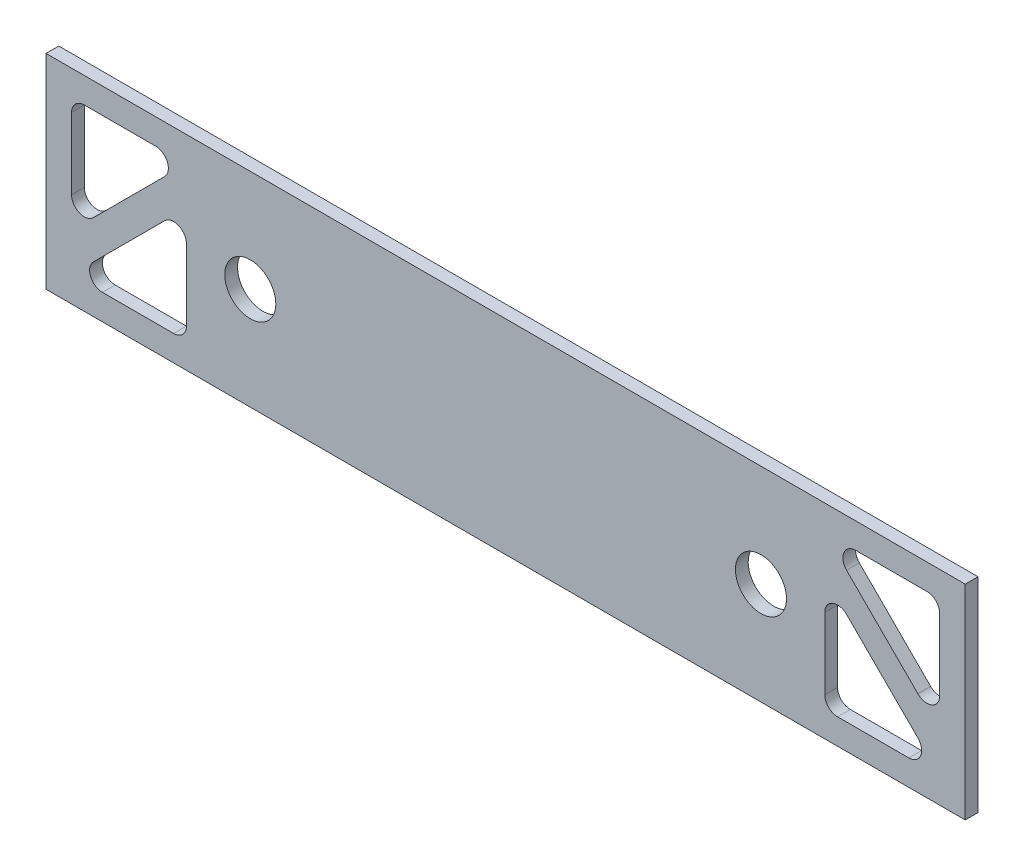
SolidWorks part; units mm, degrees
material "1060 Alloy"
ref_plane "Front Plane" through (0, 0, 0) normal (0, 0, 1) x (1, 0, 0)
ref_plane "Top Plane" through (0, 0, 0) normal (0, 1, 0) x (1, 0, 0)
ref_plane "Right Plane" through (0, 0, 0) normal (1, 0, 0) x (0, 0, -1)
sketch "Sketch1" plane through (0, 0, 0) normal (1, 0, 0) x (0, 0, -1)
  line L1 (5.0884, 8.6191) -> (-1.2616, 8.6191)
  line L2 (5.0884, 8.6191) -> (5.0884, -92.9809)
  line L3 (5.0884, -92.9809) -> (-1.2616, -92.9809)
  line L4 (-1.2616, 8.6191) -> (-1.2616, -92.9809)
  dimension "D1" = 6.35
  dimension "D2" = 101.6
extrude "Boss-Extrude1" add sketch "Sketch1" along normal blind 457.2
sketch "Sketch2" plane through (0, 0, -5.0884) normal (0, 0, -1) x (-1, 0, 0)
  line L0 (-457.2, 8.6191) -> (0, 8.6191) construction
  line L1 (0, -92.9809) -> (0, 8.6191) construction
  line L2 (-457.2, -92.9809) -> (-457.2, 8.6191) construction
  circle A0 centre (-355.6, -42.1809) radius 12.7
  circle A1 centre (-101.6, -42.1809) radius 12.7
  dimension "D1" = 25.4
  dimension "D2" = 25.4
  dimension "D3" = 50.8
  dimension "D4" = 50.8
  dimension "D5" = 101.6
  dimension "D6" = 101.6
extrude "Cut-Extrude1" cut sketch "Sketch2" against normal through all
sketch "Sketch3" plane through (0, 0, -5.0884) normal (0, 0, -1) x (-1, 0, 0)
  line L0 (-438.15, -4.0809) -> (-402.6803, -4.0809)
  line L1 (-444.5, -10.4309) -> (-444.5, -45.9006)
  line L2 (-433.6599, -50.3907) -> (-398.1901, -14.921)
  line L3 (-398.1901, -33.971) -> (-433.6599, -69.4407)
  line L4 (-429.1697, -80.2809) -> (-393.7, -80.2809)
  line L5 (-387.35, -73.9309) -> (-387.35, -38.4611)
  line L6 (-457.2, 8.6191) -> (0, 8.6191) construction
  line L7 (-457.2, -92.9809) -> (-457.2, 8.6191) construction
  line L8 (-457.2, -92.9809) -> (0, -92.9809) construction
  line L9 (-228.6, 8.6191) -> (-228.6, -92.9809) construction
  line L10 (-69.85, -73.9309) -> (-69.85, -38.4611)
  line L11 (-28.0303, -80.2809) -> (-63.5, -80.2809)
  line L12 (-59.0099, -33.971) -> (-23.5401, -69.4407)
  line L13 (-23.5401, -50.3907) -> (-59.0099, -14.921)
  line L14 (-12.7, -10.4309) -> (-12.7, -45.9006)
  line L15 (-19.05, -4.0809) -> (-54.5197, -4.0809)
  arc A0 (-398.1901, -33.971) -> (-387.35, -38.4611) centre (-393.7, -38.4611) cw
  arc A1 (-393.7, -80.2809) -> (-387.35, -73.9309) centre (-393.7, -73.9309) ccw
  arc A2 (-433.6599, -69.4407) -> (-429.1697, -80.2809) centre (-429.1697, -73.9309) ccw
  arc A3 (-444.5, -45.9006) -> (-433.6599, -50.3907) centre (-438.15, -45.9006) ccw
  arc A4 (-402.6803, -4.0809) -> (-398.1901, -14.921) centre (-402.6803, -10.4309) cw
  arc A5 (-438.15, -4.0809) -> (-444.5, -10.4309) centre (-438.15, -10.4309) ccw
  arc A6 (-19.05, -4.0809) -> (-12.7, -10.4309) centre (-19.05, -10.4309) cw
  arc A7 (-54.5197, -4.0809) -> (-59.0099, -14.921) centre (-54.5197, -10.4309) ccw
  arc A8 (-12.7, -45.9006) -> (-23.5401, -50.3907) centre (-19.05, -45.9006) cw
  arc A9 (-23.5401, -69.4407) -> (-28.0303, -80.2809) centre (-28.0303, -73.9309) cw
  arc A10 (-63.5, -80.2809) -> (-69.85, -73.9309) centre (-63.5, -73.9309) cw
  arc A11 (-59.0099, -33.971) -> (-69.85, -38.4611) centre (-63.5, -38.4611) ccw
  point P17 (-387.35, -80.2809)
  point P20 (-444.5, -80.2809)
  point P23 (-444.5, -61.2309)
  point P26 (-387.35, -4.0809)
  point P29 (-444.5, -4.0809)
  point P50 (-12.7, -4.0809)
  point P51 (-69.85, -4.0809)
  point P52 (-12.7, -61.2309)
  point P53 (-12.7, -80.2809)
  point P54 (-69.85, -80.2809)
  dimension "D8" = 6.35
  dimension "D1" = 12.7
  dimension "D2" = 12.7
  dimension "D3" = 12.7
  dimension "D4" = 12.7
  dimension "D5" = 57.15
  dimension "D6" = 57.15
  dimension "D7" = 57.15
extrude "Cut-Extrude2" cut sketch "Sketch3" against normal through all
